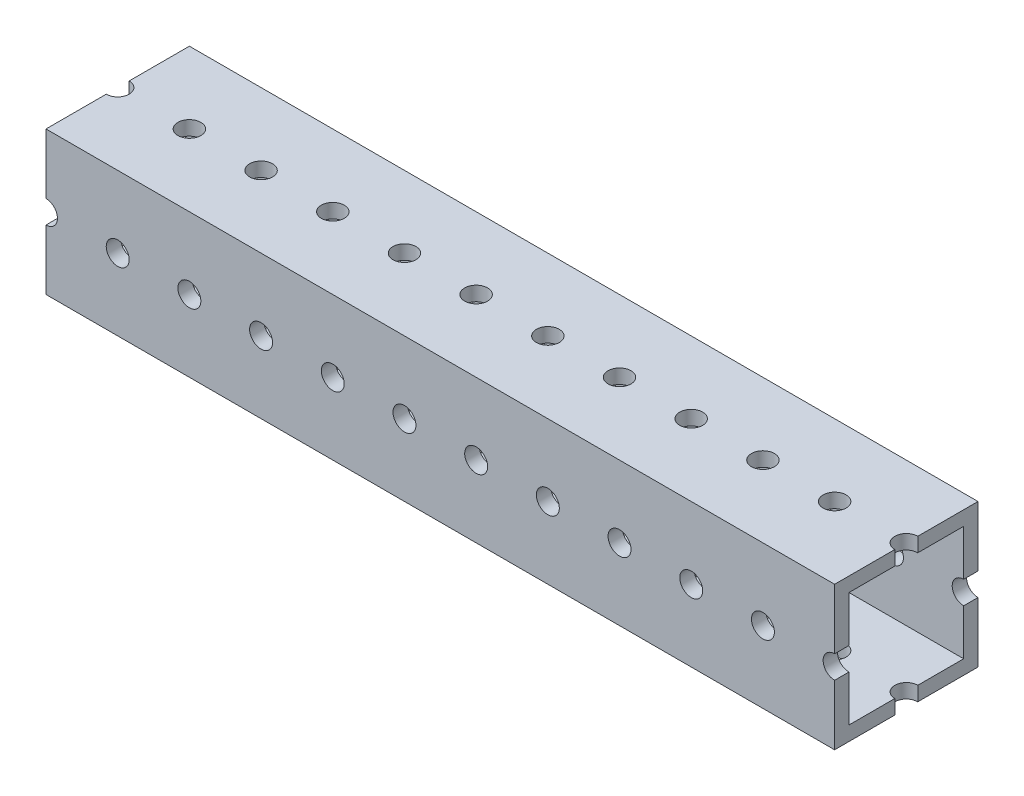
SolidWorks part; units mm, degrees
ref_plane "Front Plane" through (0, 0, 0) normal (0, 0, 1) x (1, 0, 0)
ref_plane "Top Plane" through (0, 0, 0) normal (0, 1, 0) x (1, 0, 0)
ref_plane "Right Plane" through (0, 0, 0) normal (1, 0, 0) x (0, 0, -1)
sketch "Sketch1" plane through (0, 0, 0) normal (1, 0, 0) x (0, 0, -1)
  line L0 (-10.16, 10.16) -> (10.16, 10.16)
  line L1 (-12.7, -12.7) -> (12.7, -12.7)
  line L2 (-12.7, -12.7) -> (-12.7, 12.7)
  line L3 (-12.7, 12.7) -> (12.7, 12.7)
  line L4 (12.7, -12.7) -> (12.7, 12.7)
  line L5 (-12.7, -12.7) -> (12.7, 12.7) construction
  line L6 (-12.7, 12.7) -> (12.7, -12.7) construction
  line L7 (10.16, -10.16) -> (10.16, 10.16)
  line L8 (-10.16, -10.16) -> (10.16, -10.16)
  line L9 (-10.16, -10.16) -> (-10.16, 10.16)
  point P0 (0, 0)
  dimension "D1" = 25.4
  dimension "D2" = 25.4
  dimension "D3" = 2.54
extrude "Boss-Extrude1" add sketch "Sketch1" along normal blind 139.7
sketch "Sketch2" plane through (0, 12.7, 0) normal (0, 1, 0) x (1, 0, 0)
  line L0 (0, 12.7) -> (0, -12.7) construction
  circle A0 centre (0, 0) radius 2.032
  circle A1 centre (12.7, 0) radius 2.032
  circle A2 centre (25.4, 0) radius 2.032
  circle A3 centre (38.1, 0) radius 2.032
  circle A4 centre (50.8, 0) radius 2.032
  circle A5 centre (63.5, 0) radius 2.032
  circle A6 centre (76.2, 0) radius 2.032
  circle A7 centre (88.9, 0) radius 2.032
  circle A8 centre (101.6, 0) radius 2.032
  circle A9 centre (114.3, 0) radius 2.032
  circle A10 centre (127, 0) radius 2.032
  circle A11 centre (139.7, 0) radius 2.032
  circle A12 centre (152.4, 0) radius 2.032
  circle A13 centre (165.1, 0) radius 2.032
  circle A14 centre (177.8, 0) radius 2.032
  circle A15 centre (190.5, 0) radius 2.032
  dimension "D1" = 4.064
  dimension "D2" = 16
extrude "Cut-Extrude1" cut sketch "Sketch2" against normal through all
sketch "Sketch3" plane through (0, 0, -12.7) normal (0, 0, -1) x (-1, 0, 0)
  line L0 (0, -12.7) -> (0, 12.7) construction
  circle A0 centre (0, 0) radius 2.032
  circle A1 centre (-12.7, 0) radius 2.032
  circle A2 centre (-25.4, 0) radius 2.032
  circle A3 centre (-38.1, 0) radius 2.032
  circle A4 centre (-50.8, 0) radius 2.032
  circle A5 centre (-63.5, 0) radius 2.032
  circle A6 centre (-76.2, 0) radius 2.032
  circle A7 centre (-88.9, 0) radius 2.032
  circle A8 centre (-101.6, 0) radius 2.032
  circle A9 centre (-114.3, 0) radius 2.032
  circle A10 centre (-127, 0) radius 2.032
  circle A11 centre (-139.7, 0) radius 2.032
  circle A12 centre (-152.4, 0) radius 2.032
  circle A13 centre (-165.1, 0) radius 2.032
  circle A14 centre (-177.8, 0) radius 2.032
  circle A15 centre (-190.5, 0) radius 2.032
  circle A16 centre (-203.2, 0) radius 2.032
  dimension "D1" = 4.064
  dimension "D2" = 17
extrude "Cut-Extrude2" cut sketch "Sketch3" against normal through all
